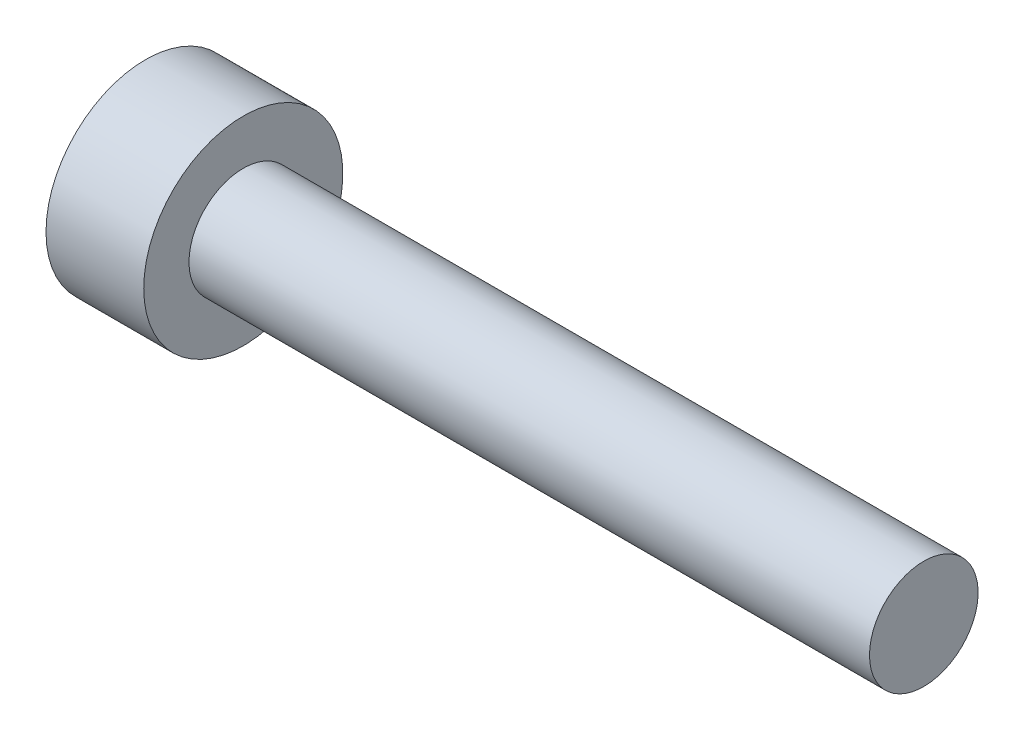
SolidWorks part; units mm, degrees
ref_plane "Front Plane" through (0, 0, 0) normal (0, 0, 1) x (1, 0, 0)
ref_plane "Top Plane" through (0, 0, 0) normal (0, 1, 0) x (1, 0, 0)
ref_plane "Right Plane" through (0, 0, 0) normal (1, 0, 0) x (0, 0, -1)
sketch "Axial profile (mm)" plane through (0, 0, 0) normal (0, 0, 1) x (1, 0, 0)
  line L0 (-110, 0) -> (75, 0) construction
  line L1 (146, 0) -> (167.5, 0)
  line L2 (167.5, 0) -> (167.5, 1.5)
  line L3 (167.5, 1.5) -> (148.7, 1.5)
  line L4 (148.7, 1.5) -> (148.7, 2.75)
  line L5 (148.7, 2.75) -> (146, 2.75)
  line L6 (146, 2.75) -> (146, 0)
revolve "Full revolution" add sketch "Axial profile (mm)" angle 360 about L0
